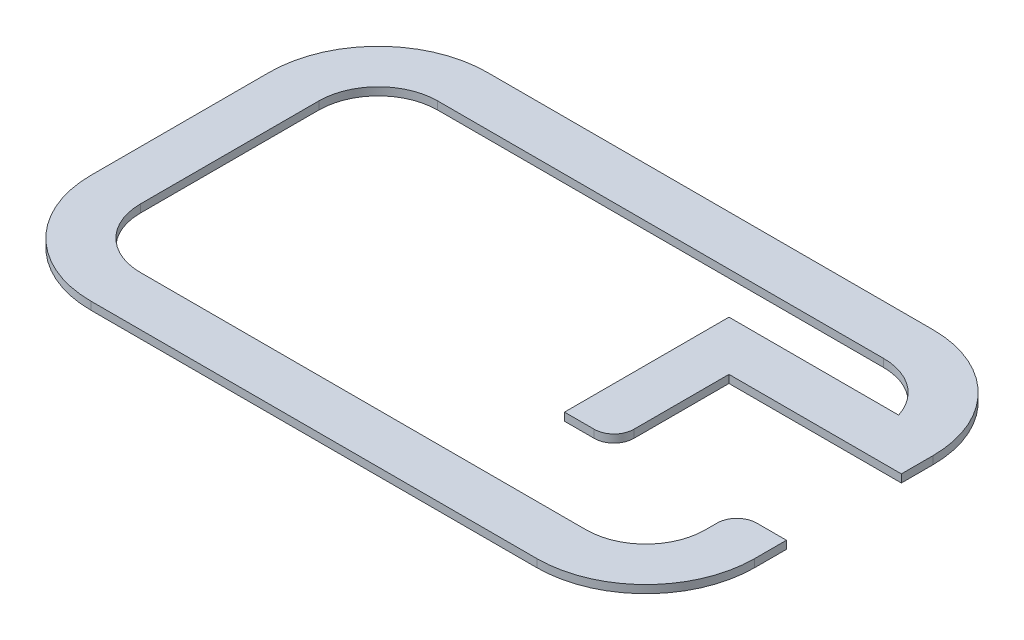
SolidWorks part; units mm, degrees
ref_plane "Front Plane" through (0, 0, 0) normal (0, 0, 1) x (1, 0, 0)
ref_plane "Top Plane" through (0, 0, 0) normal (0, 1, 0) x (1, 0, 0)
ref_plane "Right Plane" through (0, 0, 0) normal (1, 0, 0) x (0, 0, -1)
sketch "Sketch1" plane through (0, 0, 0) normal (0, 1, 0) x (1, 0, 0)
  line L0 (223, 154) -> (223, 71)
  line L1 (55, 0) -> (280, 0)
  line L2 (0, 55) -> (0, 145)
  line L3 (55, 200) -> (280, 200)
  line L4 (335, 145) -> (335, 129)
  line L5 (335, 55) -> (335, 71)
  line L6 (308.6182, 154) -> (223, 154)
  line L7 (308.6182, 154) -> (308.6182, 154)
  line L8 (335, 129) -> (248, 129)
  line L9 (55, 175) -> (280, 175)
  line L10 (25, 55) -> (25, 145)
  line L11 (248, 129) -> (248, 81)
  line L12 (55, 25) -> (280, 25)
  line L13 (310, 55) -> (310, 61)
  line L14 (223, 71) -> (238, 71)
  line L15 (320, 71) -> (335, 71)
  line L16 (310, 55) -> (310, 71) construction
  line L17 (248, 129) -> (248, 71) construction
  arc A0 (55, 0) -> (0, 55) centre (55, 55) cw
  arc A1 (280, 0) -> (335, 55) centre (280, 55) ccw
  arc A2 (280, 200) -> (335, 145) centre (280, 145) cw
  arc A3 (0, 145) -> (55, 200) centre (55, 145) cw
  arc A4 (280, 175) -> (308.6182, 154) centre (280, 145) cw
  arc A5 (25, 145) -> (55, 175) centre (55, 145) cw
  arc A6 (55, 25) -> (25, 55) centre (55, 55) cw
  arc A7 (280, 25) -> (310, 55) centre (280, 55) ccw
  arc A8 (310, 61) -> (320, 71) centre (320, 61) cw
  arc A9 (248, 81) -> (238, 71) centre (238, 81) cw
  point P7 (0, 0)
  point P15 (0, 200)
  point P42 (248, 71)
  dimension "D3" = 55
  dimension "D7" = 87
  dimension "D6" = 10
  dimension "D8" = 10
  dimension "D1" = 335
  dimension "D2" = 200
  dimension "D5" = 58
  dimension "D9" = 16
  dimension "D10" = 16
  dimension "D4" = 25
extrude "Boss-Extrude1" add sketch "Sketch1" along normal blind 4
